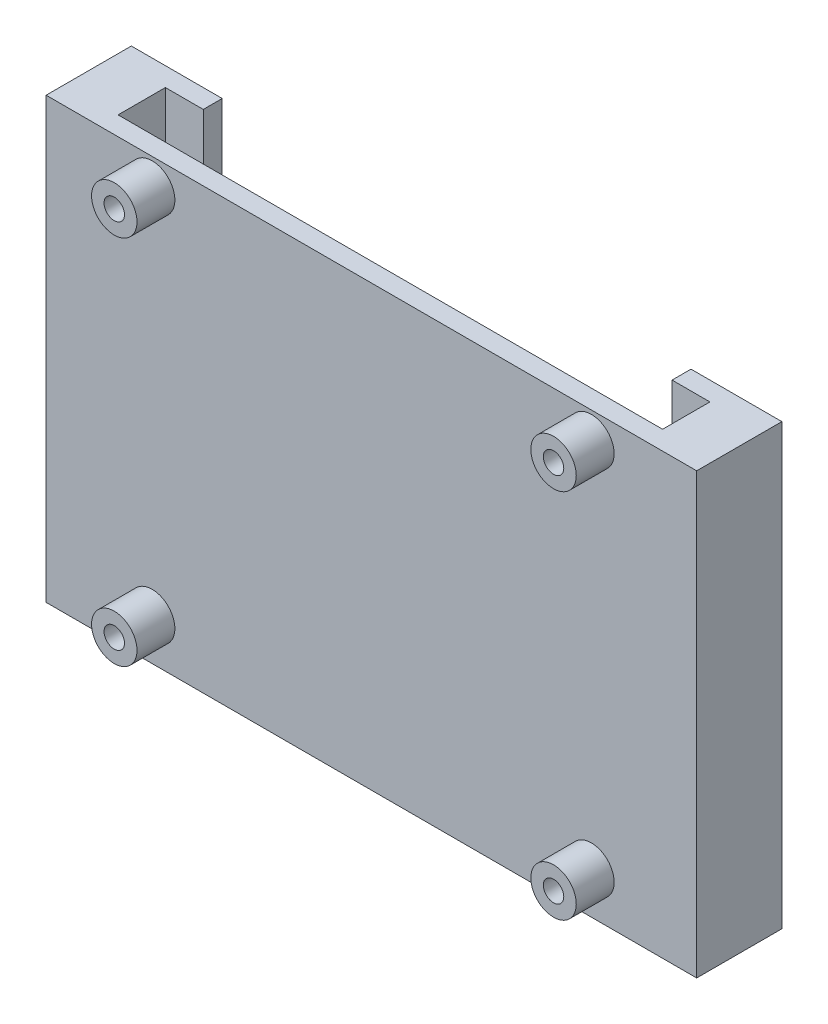
SolidWorks part; units mm, degrees
ref_plane "Front Plane" through (0, 0, 0) normal (0, 0, 1) x (1, 0, 0)
ref_plane "Top Plane" through (0, 0, 0) normal (0, 1, 0) x (1, 0, 0)
ref_plane "Right Plane" through (0, 0, 0) normal (1, 0, 0) x (0, 0, -1)
sketch "Sketch1" plane through (0, 0, 0) normal (0, 0, 1) x (1, 0, 0)
  line L1 (-42.95, -29) -> (42.95, -29)
  line L2 (-42.95, -29) -> (-42.95, 29)
  line L3 (-42.95, 29) -> (42.95, 29)
  line L4 (42.95, -29) -> (42.95, 29)
  line L5 (-42.95, -29) -> (42.95, 29) construction
  line L6 (-42.95, 29) -> (42.95, -29) construction
  point P0 (0, 0)
  dimension "D1" = 85.9
  dimension "D2" = 58
extrude "Boss-Extrude1" add sketch "Sketch1" along normal blind 2.5
sketch "Sketch2" plane through (0, 0, 2.5) normal (0, 0, 1) x (1, 0, 0)
  line L0 (42.95, 29) -> (-42.95, 29) construction
  line L1 (-42.95, 29) -> (-42.95, -29) construction
  circle A0 centre (-28.95, 25.5) radius 3
  circle A1 centre (29.05, 25.5) radius 3
  point P8 (0, 0)
  point P9 (0, 0)
  dimension "D1" = 6
  dimension "D4" = 58
  dimension "D2" = 3.5
  dimension "D3" = 14
extrude "Boss-Extrude2" add sketch "Sketch2" along normal blind 5
pattern_linear "LPattern1" count 2 spacing 49 along (0, -1, 0) of "Boss-Extrude2"
sketch "Sketch3" plane through (0, 0, 7.5) normal (0, 0, 1) x (1, 0, 0)
  circle A0 centre (-28.95, -23.5) radius 3 construction
  circle A1 centre (29.05, 25.5) radius 3 construction
  circle A2 centre (29.05, -23.5) radius 3 construction
  point P0 (-28.95, 25.5)
  point P3 (-28.95, -23.5)
  point P10 (29.05, 25.5)
  point P12 (29.05, -23.5)
  point P15 (0, 0)
  point P18 (0, 0)
hole_wizard "M2.5 Clearance Hole1" positions "Sketch3" profile "Sketch4" hole size "M2.5" standard "ANSI Metric" end condition through all
sketch "Sketch4" plane through (-28.95, 25.5, 7.5) normal (1, 0, 0) x (0, -1, 0)
  line L0 (0, 0) -> (0, 7.5)
  line L1 (0, 7.5) -> (1.35, 7.5)
  line L2 (1.35, 7.5) -> (1.35, 0)
  line L5 (1.35, 0) -> (0, 0)
  line L11 (0, -6.35) -> (0, 107.95) construction
  dimension "Thru Hole Dia." = 2.7
  dimension "Thru Hole Depth" = 7.5
sketch "Sketch6" plane through (0, 0, 0) normal (0, 0, -1) x (-1, 0, 0)
  line L0 (42.95, -29) -> (-42.95, -29) construction
  line L1 (-42.95, 29) -> (-35.95, 29)
  line L2 (-42.95, 29) -> (-42.95, -29)
  line L3 (-42.95, -29) -> (-35.95, -29)
  line L4 (-35.95, 29) -> (-35.95, -29)
  line L6 (42.95, 29) -> (35.95, 29)
  line L7 (42.95, 29) -> (42.95, -29)
  line L8 (42.95, -29) -> (35.95, -29)
  line L9 (35.95, 29) -> (35.95, -29)
  dimension "D1" = 7
  dimension "D2" = 7
extrude "Boss-Extrude3" add sketch "Sketch6" along normal blind 8.75
sketch "Sketch7" plane through (35.95, 0, 0) normal (-1, 0, 0) x (0, 0, 1)
  line L0 (2.5, -29) -> (-8.75, -29) construction
  line L1 (-8.75, 29) -> (-6.25, 29)
  line L2 (-8.75, 29) -> (-8.75, -29)
  line L3 (-8.75, -29) -> (-6.25, -29)
  line L4 (-6.25, 29) -> (-6.25, -29)
  dimension "D1" = 2.5
extrude "Boss-Extrude4" add sketch "Sketch7" along normal blind 5
sketch "Sketch8" plane through (-35.95, 0, 0) normal (1, 0, 0) x (0, 0, -1)
  line L1 (8.75, 29) -> (6.25, 29)
  line L2 (8.75, 29) -> (8.75, -29)
  line L3 (8.75, -29) -> (6.25, -29)
  line L4 (6.25, 29) -> (6.25, -29)
extrude "Boss-Extrude5" add sketch "Sketch8" along normal blind 5
sketch "Sketch9" plane through (0, -29, 0) normal (0, -1, 0) x (1, 0, 0)
  line L0 (-42.95, -3.125) -> (42.95, -3.125) construction
  line L1 (-42.95, 2.5) -> (-42.95, -8.75) construction
  line L2 (42.95, 2.5) -> (42.95, -8.75) construction
  line L3 (-35.95, 0) -> (-42.95, 0) construction
  line L4 (-39.45, 0) -> (-39.45, -8.75) construction
  line L5 (-30.95, -8.75) -> (-42.95, -8.75) construction
  line L6 (35.95, 0) -> (42.95, 0) construction
  line L7 (39.45, 0) -> (39.45, -8.75) construction
  line L8 (42.95, -8.75) -> (30.95, -8.75) construction
  circle A0 centre (-39.45, -3.125) radius 3.15
  circle A1 centre (39.45, -3.125) radius 3.15
  point P25 (0, 0)
  dimension "D1" = 6.3
  dimension "D2" = 6.3
extrude "Cut-Extrude1" cut sketch "Sketch9" against normal blind 2.7
